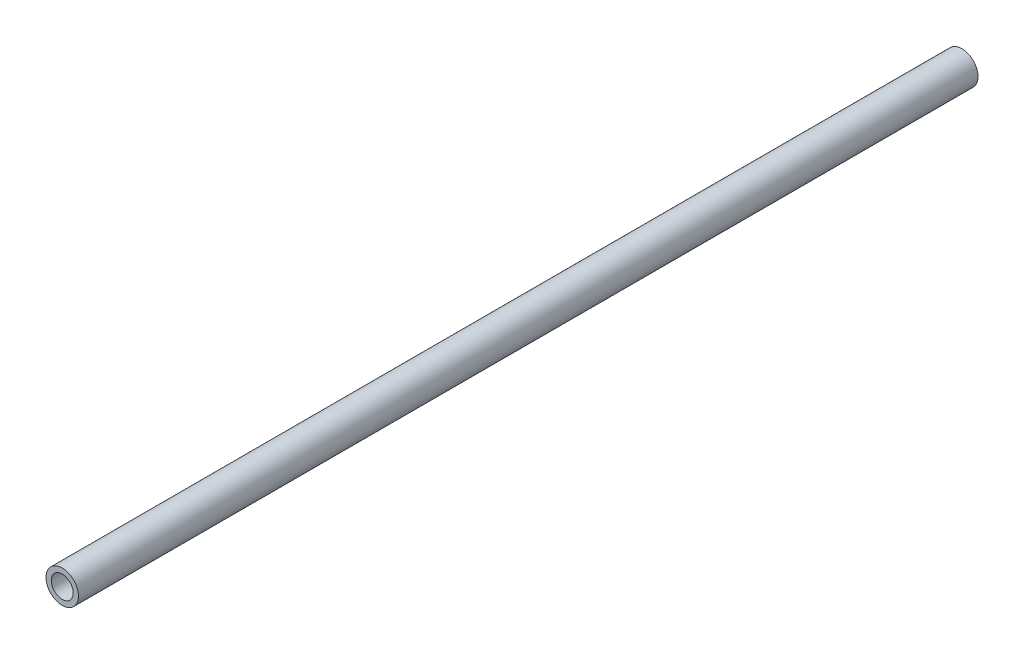
SolidWorks part; units mm, degrees
ref_plane "Front Plane" through (0, 0, 0) normal (0, 0, 1) x (1, 0, 0)
ref_plane "Top Plane" through (0, 0, 0) normal (0, 1, 0) x (1, 0, 0)
ref_plane "Right Plane" through (0, 0, 0) normal (1, 0, 0) x (0, 0, -1)
sketch "Sketch2" plane through (0, 0, 0) normal (0, 0, 1) x (1, 0, 0)
  circle A1 centre (29.1956, 164.15) radius 11
  circle A2 centre (29.1956, 164.15) radius 12.5
  circle A3 centre (29.1956, 164.15) radius 12.5
  circle A4 centre (29.1956, 164.15) radius 11
  circle A5 centre (29.1956, 164.15) radius 7.444
  dimension "D3" = 22
  dimension "D1" = 0
  dimension "D2" = 0
  dimension "D4" = 3.556
extrude "Boss-Extrude1" add sketch "Sketch2" along normal blind 609.6 contours A1 A5
